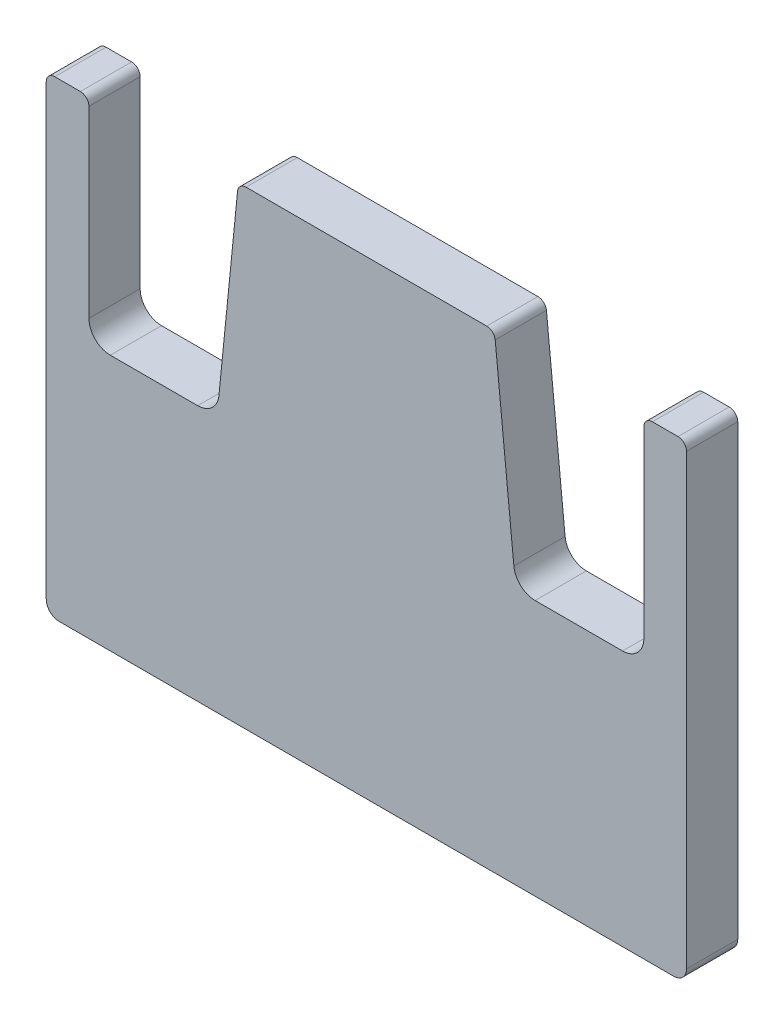
SolidWorks part; units mm, degrees
ref_plane "Plan de face" through (0, 0, 0) normal (0, 0, 1) x (1, 0, 0)
ref_plane "Plan de dessus" through (0, 0, 0) normal (0, 1, 0) x (1, 0, 0)
ref_plane "Plan de droite" through (0, 0, 0) normal (1, 0, 0) x (0, 0, -1)
sketch "Esquisse1" plane through (0, 0, 0) normal (0, 0, 1) x (1, 0, 0)
  line L0 (0, 0) -> (150, 0)
  line L1 (150, 0) -> (150, 110)
  line L2 (150, 110) -> (0, 110)
  line L3 (75, 110) -> (75, 0) construction
  line L4 (0, 0) -> (0, 110)
  dimension "D1" = 110
  dimension "D2" = 150
  dimension "D3" = 150
extrude "Boss.-Extru.1" add sketch "Esquisse1" along normal blind 12
sketch "Esquisse2" plane through (0, 0, 12) normal (0, 0, 1) x (1, 0, 0)
  line L0 (75, 110) -> (75, 0) construction
  line L1 (150, 110) -> (0, 110) construction
  line L2 (0, 0) -> (150, 0) construction
  line L3 (105, 110) -> (110, 60)
  line L4 (10, 110) -> (45, 110)
  line L5 (10, 110) -> (10, 60)
  line L6 (10, 60) -> (40, 60)
  line L7 (45, 110) -> (40, 60)
  line L8 (140, 60) -> (110, 60)
  line L9 (140, 110) -> (140, 60)
  line L10 (140, 110) -> (105, 110)
  point P20 (0, 110)
  dimension "D1" = 35
  dimension "D2" = 30
  dimension "D3" = 50
  dimension "D4" = 10
extrude "Enlèv. mat.-Extru.1" cut sketch "Esquisse2" against normal through all both and the other way through all
fillet "Congé1" radius 5 4 edges at (140, 60, 6) (110, 60, 6) (40, 60, 6) (10, 60, 6)
sketch "Esquisse3" plane through (0, 0, 12) normal (0, 0, 1) x (1, 0, 0)
  line L0 (75, 0) -> (75, 30) construction
  line L1 (0, 0) -> (150, 0) construction
  line L2 (75, 30) -> (25, 30) construction
  circle A0 centre (25, 30) radius 3.25
  circle A1 centre (125, 30) radius 3.25
  dimension "D1" = 6.5
  dimension "D2" = 100
  dimension "D3" = 30
extrude "Enlèv. mat.-Extru.2" [suppressed] cut sketch "Esquisse3" against normal through all both and the other way through all
fillet "Congé2" radius 2 6 edges at (150, 110, 6) (0, 110, 6) (140, 110, 6) (105, 110, 6) (45, 110, 6) (10, 110, 6)
fillet "Congé3" radius 3 2 edges at (150, 0, 6) (0, 0, 6)
chamfer "Chanfrein1" [suppressed] distance 4 angle 45
